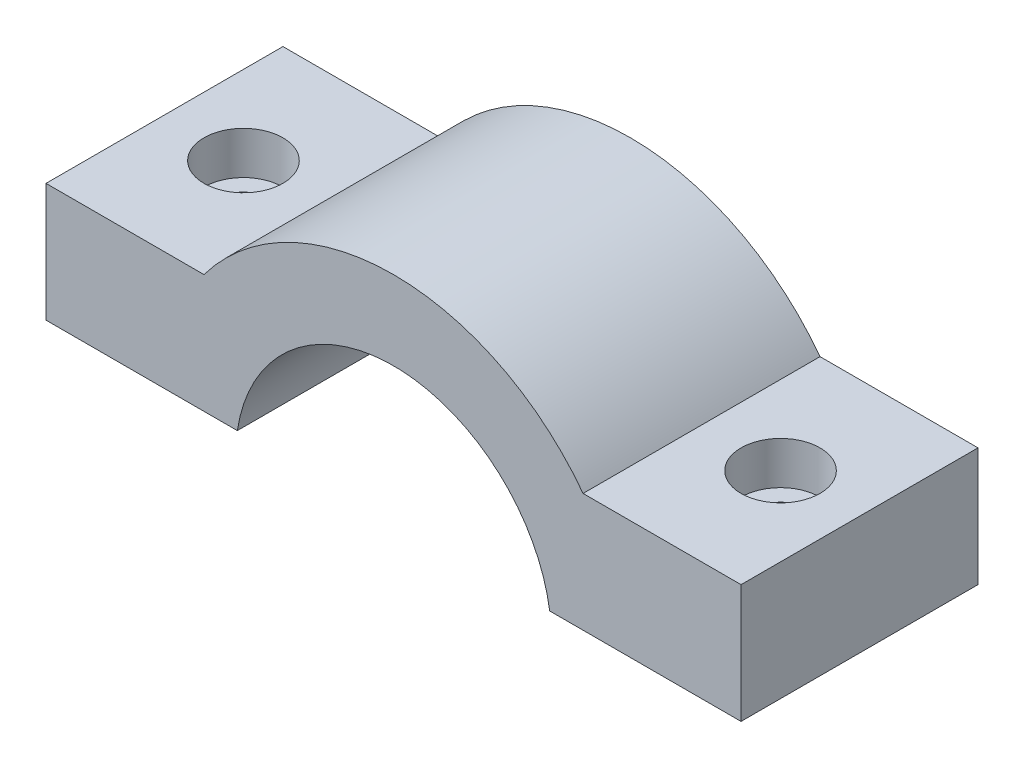
SolidWorks part; units mm, degrees
ref_plane "Plan de face" through (0, 0, 0) normal (0, 0, 1) x (1, 0, 0)
ref_plane "Plan de dessus" through (0, 0, 0) normal (0, 1, 0) x (1, 0, 0)
ref_plane "Plan de droite" through (0, 0, 0) normal (1, 0, 0) x (0, 0, -1)
sketch "Esquisse1" plane through (0, 0, 0) normal (0, 0, 1) x (1, 0, 0)
  line L0 (43.3831, -1.0708) -> (67.6094, -1.0708)
  line L1 (107.1568, -1.0708) -> (131.3831, -1.0708)
  line L2 (131.3831, -1.0708) -> (131.3831, 13.9292)
  line L3 (131.3831, 13.9292) -> (111.3831, 13.9292)
  line L4 (43.3831, -1.0708) -> (43.3831, 13.9292)
  line L5 (43.3831, 13.9292) -> (63.3831, 13.9292)
  circle A0 centre (87.3831, -4.0708) radius 20 construction
  arc A1 (67.6094, -1.0708) -> (107.1568, -1.0708) centre (87.3831, -4.0708) cw
  arc A2 (63.3831, 13.9292) -> (111.3831, 13.9292) centre (87.3831, -4.0708) cw
  dimension "D1" = 10
  dimension "D2" = 15
  dimension "D3" = 20
  dimension "D4" = 20
  dimension "D5" = 3
extrude "Boss.-Extru.1" add sketch "Esquisse1" along normal mid plane 30 contours A2 L3 L2 L1 A1 L0 L4 L5
hole_wizard "Chambrage pour vis à tête hexagonale M51" positions "Esquisse3D1" profile "Esquisse2" counterbore size "M5" standard "ISO" end condition through all
sketch3d "Esquisse3D1"
  line L0 (43.3831, 13.9292, -15) -> (63.3831, 13.9292, 15) construction
  line L2 (111.3831, 13.9292, -15) -> (131.3831, 13.9292, 15) construction
  point P0 (53.3831, 13.9292, 0)
  point P2 (121.3831, 13.9292, 0)
  point P15 (0, 0, 0)
  point P16 (0, 0, 0)
sketch "Esquisse2" plane through (53.3831, 13.9292, 0) normal (1, 0, 0) x (0, 0, 1)
  line L0 (0, 0) -> (0, 15)
  line L1 (0, 15) -> (2.75, 15)
  line L3 (2.75, 15) -> (2.75, 5.4)
  line L4 (2.75, 5.4) -> (5, 5.4)
  line L5 (5, 5.4) -> (5, 0)
  line L7 (5, 0) -> (0, 0)
  line L11 (0, -6.35) -> (0, 107.95) construction
  dimension "Diamètre du perçage jusqu'au prochain" = 5.5
  dimension "Profondeur du perçage jusqu'au prochain" = 15
  dimension "Diamètre du chambrage" = 10
  dimension "Profondeur du chambrage" = 5.4
